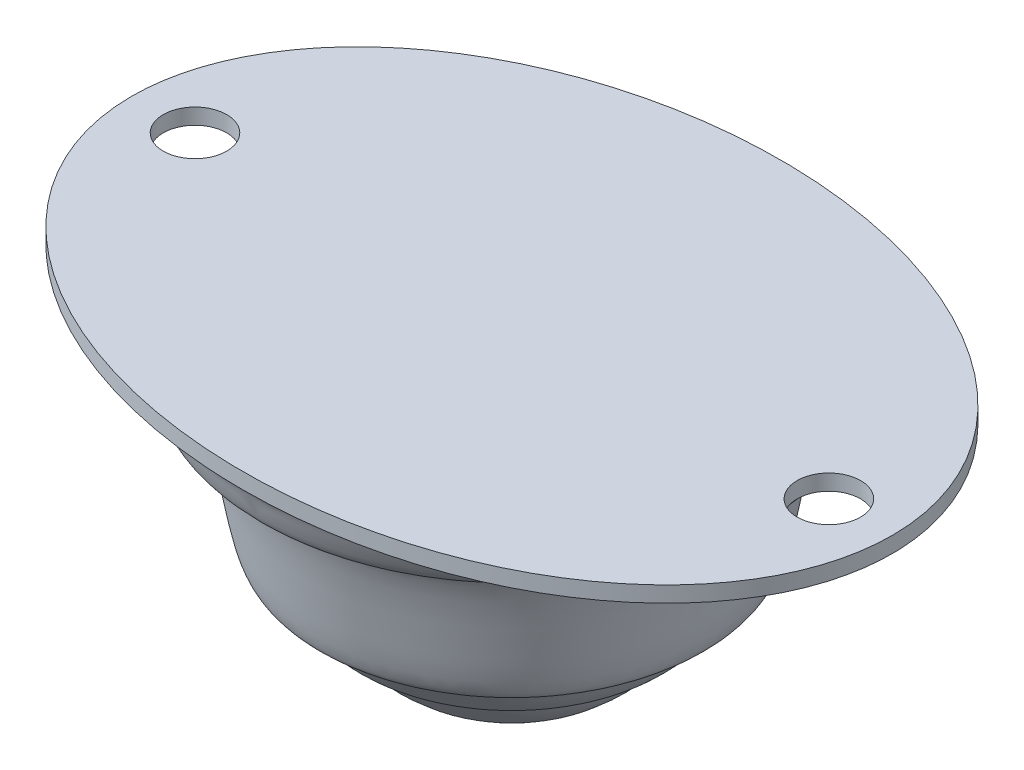
SolidWorks part; units mm, degrees
ref_plane "Front" through (0, 0, 0) normal (0, 0, 1) x (1, 0, 0)
ref_plane "Top" through (0, 0, 0) normal (0, 1, 0) x (1, 0, 0)
ref_plane "Right" through (0, 0, 0) normal (1, 0, 0) x (0, 0, -1)
sketch "Sketch1" plane through (0, 0, 0) normal (0, 0, 1) x (1, 0, 0)
  line L0 (17, 0) -> (0, 0)
  line L1 (0, 0) -> (0, -19)
  arc A0 (8.7821, -13.881) -> (0, -19) centre (0, -8.9072) cw
  spline S0 degree 3 poles (17, 0) (16.4988, -0.2323) (16.2214, -3.077) (13.3179, -2.2736) (12.7657, -12.146) (11.3651, -11.2439) (10.4224, -12.693) (8.5497, -15.111) (9.2438, -11.3266) (8.7821, -13.881) knots 0 0 0 0 0.23512 0.368864 0.707611 0.794741 0.873855 0.920942 1 1 1 1
  dimension "D1" = 19
  dimension "D2" = 17
  dimension "D3" = 5
revolve "Revolve1" add sketch "Sketch1" angle 360 about L1
sketch "Sketch2" plane through (0, 0, 0) normal (0, 1, 0) x (1, 0, 0)
  circle A0 centre (0, 0) radius 17 construction
  circle A1 centre (-20, 0) radius 2
  circle A2 centre (20, 0) radius 2
  ellipse E0 centre (0, 0) end of major axis (24, 0) minor radius 17
  dimension "D1" = 4
  dimension "D2" = 20
  dimension "D3" = 40
  dimension "D4" = 4
extrude "Boss-Extrude1" add sketch "Sketch2" along normal blind 1
